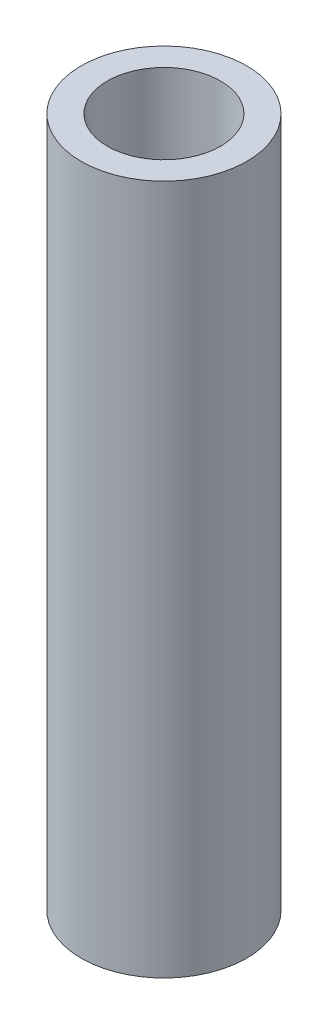
SolidWorks part; units mm, degrees
material "6061 Alloy"
ref_plane "Front Plane" through (0, 0, 0) normal (0, 0, 1) x (1, 0, 0)
ref_plane "Top Plane" through (0, 0, 0) normal (0, 1, 0) x (1, 0, 0)
ref_plane "Right Plane" through (0, 0, 0) normal (1, 0, 0) x (0, 0, -1)
sketch "Sketch1" plane through (0, 0, 0) normal (0, 1, 0) x (1, 0, 0)
  circle A0 centre (0, 0) radius 4.1
  circle A1 centre (0, 0) radius 6
  dimension "D1" = 8.2
  dimension "D2" = 12
extrude "Boss-Extrude1" add sketch "Sketch1" along normal blind 50
equation "\"____ GENERATED PART EXPORTS ____\" = 0"
equation "\"SYS_VersionTag\" = 2"
equation "\"HW_SpacerID\" = 8.2mm"
equation "\"HW_SpacerOD\" = 12mm"
equation "\"HW_SpacerLen\" = 50mm"
equation "\"HW_SpacerTargetLen_ForMachining\" = 50.02mm"
equation "\"D1@Sketch1\"=\"HW_SpacerID\""
equation "\"D2@Sketch1\"=\"HW_SpacerOD\""
equation "\"D1@Boss-Extrude1\"=\"HW_SpacerLen\""
